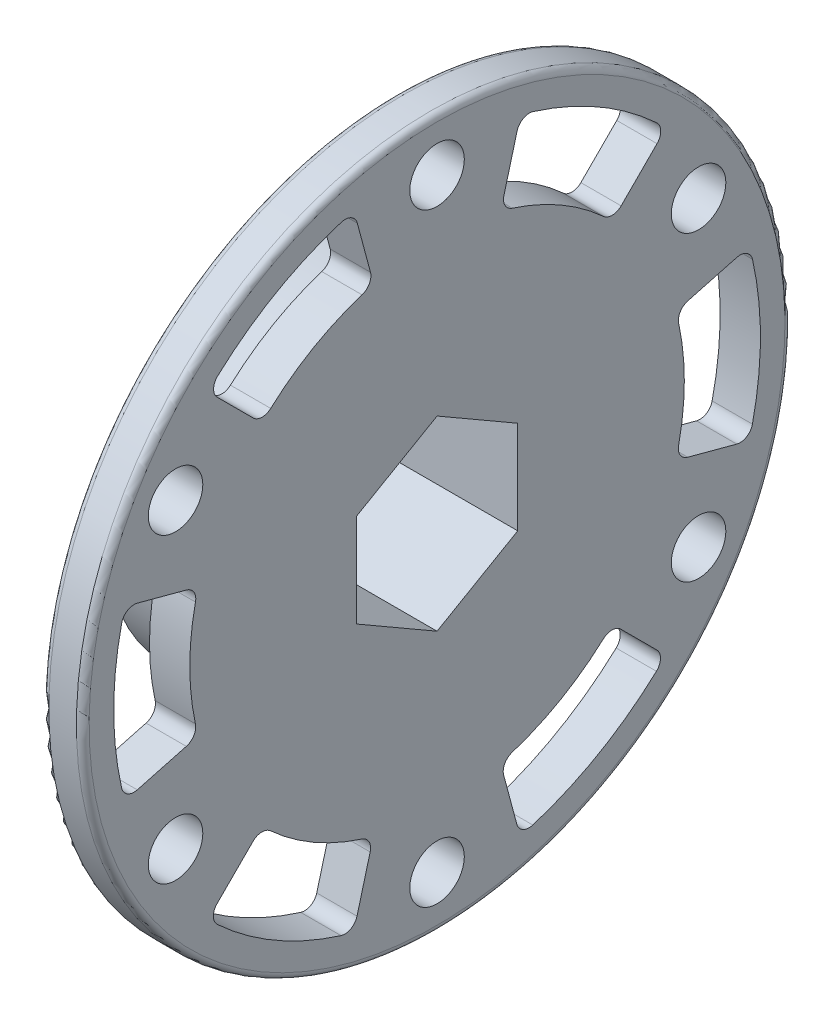
SolidWorks part; units mm, degrees
ref_plane "Front Plane" through (0, 0, 0) normal (0, 0, 1) x (1, 0, 0)
ref_plane "Top Plane" through (0, 0, 0) normal (0, 1, 0) x (1, 0, 0)
ref_plane "Right Plane" through (0, 0, 0) normal (1, 0, 0) x (0, 0, -1)
ref_plane "Plane1" through (0, 0, 0) normal (0, 0, -1) x (-1, 0, 0)
sketch "Sketch1" plane through (0, 0, 0) normal (0, 0, -1) x (-1, 0, 0)
  line L0 (-12.7, 27.94) -> (-12.7, 0)
  line L1 (-12.7, 0) -> (-9.525, 0)
  line L2 (-9.525, 0) -> (-9.525, 27.94)
  line L3 (-9.525, 27.94) -> (-12.7, 27.94)
  line L4 (-12.7, 0) -> (-9.525, 0) construction
revolve "Revolve1" add sketch "Sketch1" angle 360 about L4
sketch "Sketch2" plane through (9.525, 0, 0) normal (-1, 0, 0) x (0, 0, 1)
  line L0 (-13.8065, -13.7706) -> (-18.0492, -18.0133)
  line L1 (-6.5508, -24.6442) -> (-4.9979, -18.8486)
  arc A0 (-4.9979, -18.8486) -> (-13.8065, -13.7706) centre (0, 0) cw
  arc A1 (-18.0492, -18.0133) -> (-6.5508, -24.6442) centre (0, 0) ccw
extrude "Cut-Extrude1" cut sketch "Sketch2" against normal through all
sketch "Sketch3" plane through (9.525, 0, 0) normal (-1, 0, 0) x (0, 0, 1)
  line L0 (5.0224, -18.8421) -> (6.5753, -24.6377)
  line L1 (18.0671, -17.9953) -> (13.8245, -13.7526)
  arc A0 (13.8245, -13.7526) -> (5.0224, -18.8421) centre (0, 0) cw
  arc A1 (6.5753, -24.6377) -> (18.0671, -17.9953) centre (0, 0) ccw
extrude "Cut-Extrude2" cut sketch "Sketch3" against normal through all
sketch "Sketch4" plane through (9.525, 0, 0) normal (-1, 0, 0) x (0, 0, 1)
  line L0 (18.829, -5.0715) -> (24.6245, -6.6244)
  line L1 (24.6179, 6.6489) -> (18.8223, 5.096)
  arc A0 (18.8223, 5.096) -> (18.829, -5.0715) centre (0, 0) cw
  arc A1 (24.6245, -6.6244) -> (24.6179, 6.6489) centre (0, 0) ccw
extrude "Cut-Extrude3" cut sketch "Sketch4" against normal through all
sketch "Sketch5" plane through (9.525, 0, 0) normal (-1, 0, 0) x (0, 0, 1)
  line L0 (13.8065, 13.7706) -> (18.0492, 18.0133)
  line L1 (6.5508, 24.6442) -> (4.9979, 18.8486)
  arc A0 (4.9979, 18.8486) -> (13.8065, 13.7706) centre (0, 0) cw
  arc A1 (18.0492, 18.0133) -> (6.5508, 24.6442) centre (0, 0) ccw
extrude "Cut-Extrude4" cut sketch "Sketch5" against normal through all
sketch "Sketch6" plane through (9.525, 0, 0) normal (-1, 0, 0) x (0, 0, 1)
  line L0 (-24.6179, -6.6489) -> (-18.8223, -5.096)
  line L1 (-18.829, 5.0715) -> (-24.6245, 6.6244)
  arc A0 (-18.8223, -5.096) -> (-18.829, 5.0715) centre (0, 0) cw
  arc A1 (-24.6245, 6.6244) -> (-24.6179, -6.6489) centre (0, 0) ccw
extrude "Cut-Extrude5" cut sketch "Sketch6" against normal through all
sketch "Sketch7" plane through (12.7, 0, 0) normal (1, 0, 0) x (0, 0, -1)
  line L0 (6.5753, 24.6377) -> (5.0224, 18.8421)
  line L1 (13.8245, 13.7526) -> (18.0671, 17.9953)
  arc A0 (18.0671, 17.9953) -> (6.5753, 24.6377) centre (0, 0) ccw
  arc A1 (5.0224, 18.8421) -> (13.8245, 13.7526) centre (0, 0) cw
extrude "Cut-Extrude6" cut sketch "Sketch7" against normal through all
sketch "Sketch8" plane through (9.525, 0, 0) normal (-1, 0, 0) x (0, 0, 1)
  circle A0 centre (0, 0) radius 14.2949
extrude "Boss-Extrude1" add sketch "Sketch8" along normal blind 9.525
sketch "Sketch9" plane through (12.7, 0, 0) normal (1, 0, 0) x (0, 0, -1)
  line L0 (-6.3627, 3.6735) -> (-6.3627, -3.6735)
  line L1 (-6.3627, -3.6735) -> (0, -7.347)
  line L2 (0, -7.347) -> (6.3627, -3.6735)
  line L3 (6.3627, -3.6735) -> (6.3627, 3.6735)
  line L4 (6.3627, 3.6735) -> (0, 7.347)
  line L5 (0, 7.347) -> (-6.3627, 3.6735)
extrude "Cut-Extrude7" cut sketch "Sketch9" against normal through all
sketch "Sketch10" plane through (0, 0, 0) normal (0, 0, 1) x (1, 0, 0)
  line L0 (9.525, 25.9625) -> (9.525, 23.8125)
  line L1 (9.525, 23.8125) -> (12.7, 23.8125)
  line L2 (12.7, 23.8125) -> (12.7, 25.9625)
  line L3 (12.7, 25.9625) -> (9.525, 25.9625)
  line L4 (9.525, 23.8125) -> (12.7, 23.8125) construction
revolve "Cut-Revolve1" cut sketch "Sketch10" angle 360 about L4
ref_plane "Plane2" through (0, 0, 20.6222) normal (0, 0, 1) x (1, 0, 0)
sketch "Sketch11" plane through (0, 0, 20.6222) normal (0, 0, 1) x (1, 0, 0)
  line L0 (9.525, 14.0562) -> (9.525, 11.9062)
  line L1 (9.525, 11.9062) -> (12.7, 11.9062)
  line L2 (12.7, 11.9062) -> (12.7, 14.0562)
  line L3 (12.7, 14.0562) -> (9.525, 14.0562)
  line L4 (9.525, 11.9062) -> (12.7, 11.9062) construction
revolve "Cut-Revolve2" cut sketch "Sketch11" angle 360 about L4
sketch "Sketch12" plane through (0, 0, 20.6222) normal (0, 0, 1) x (1, 0, 0)
  line L0 (9.525, -9.7563) -> (9.525, -11.9063)
  line L1 (9.525, -11.9063) -> (12.7, -11.9063)
  line L2 (12.7, -11.9063) -> (12.7, -9.7563)
  line L3 (12.7, -9.7563) -> (9.525, -9.7563)
  line L4 (9.525, -11.9063) -> (12.7, -11.9063) construction
revolve "Cut-Revolve3" cut sketch "Sketch12" angle 360 about L4
sketch "Sketch13" plane through (0, 0, 0) normal (0, 0, 1) x (1, 0, 0)
  line L0 (9.525, -21.6625) -> (9.525, -23.8125)
  line L1 (9.525, -23.8125) -> (12.7, -23.8125)
  line L2 (12.7, -23.8125) -> (12.7, -21.6625)
  line L3 (12.7, -21.6625) -> (9.525, -21.6625)
  line L4 (9.525, -23.8125) -> (12.7, -23.8125) construction
revolve "Cut-Revolve4" cut sketch "Sketch13" angle 360 about L4
ref_plane "Plane3" through (0, 0, -20.6222) normal (0, 0, 1) x (1, 0, 0)
sketch "Sketch14" plane through (0, 0, -20.6222) normal (0, 0, 1) x (1, 0, 0)
  line L0 (9.525, -9.7562) -> (9.525, -11.9062)
  line L1 (9.525, -11.9062) -> (12.7, -11.9062)
  line L2 (12.7, -11.9062) -> (12.7, -9.7562)
  line L3 (12.7, -9.7562) -> (9.525, -9.7562)
  line L4 (9.525, -11.9062) -> (12.7, -11.9062) construction
revolve "Cut-Revolve5" cut sketch "Sketch14" angle 360 about L4
sketch "Sketch15" plane through (0, 0, -20.6222) normal (0, 0, 1) x (1, 0, 0)
  line L0 (9.525, 14.0563) -> (9.525, 11.9063)
  line L1 (9.525, 11.9063) -> (12.7, 11.9063)
  line L2 (12.7, 11.9063) -> (12.7, 14.0563)
  line L3 (12.7, 14.0563) -> (9.525, 14.0563)
  line L4 (9.525, 11.9063) -> (12.7, 11.9063) construction
revolve "Cut-Revolve6" cut sketch "Sketch15" angle 360 about L4
chamfer "Chamfer1" distance 1 angle 45 1 edges at (0, -14.2949, 0)
fillet "Fillet1" radius 0.5 2 edges at (12.7, -27.94, 0) (9.525, -27.94, 0)
fillet "Fillet2" radius 1 24 edges at (11.1125, 6.6489, 24.6179) (11.1125, -17.9953, 18.0671) (11.1125, 24.6442, 6.5508) (11.1125, -18.8421, 5.0224) (11.1125, 18.8421, -5.0224) (11.1125, -5.0715, 18.829) (11.1125, 24.6377, -6.5753) (11.1125, 13.7706, 13.8065) (11.1125, 17.9953, -18.0671) (11.1125, -18.8486, -4.9979) (11.1125, 13.7526, -13.8245) (11.1125, -24.6377, 6.5753) (11.1125, 5.0715, -18.829) (11.1125, -13.7526, 13.8245) (11.1125, 6.6244, -24.6245) (11.1125, -6.6244, 24.6245) (11.1125, -6.6489, -24.6179) (11.1125, 5.096, 18.8223) (11.1125, -5.096, -18.8223) (11.1125, 18.0133, 18.0492) (11.1125, -13.7706, -13.8065) (11.1125, 18.8486, 4.9979) (11.1125, -18.0133, -18.0492) (11.1125, -24.6442, -6.5508)
fillet "Fillet3" radius 1.27 1 edges at (9.525, -14.2949, 0)
